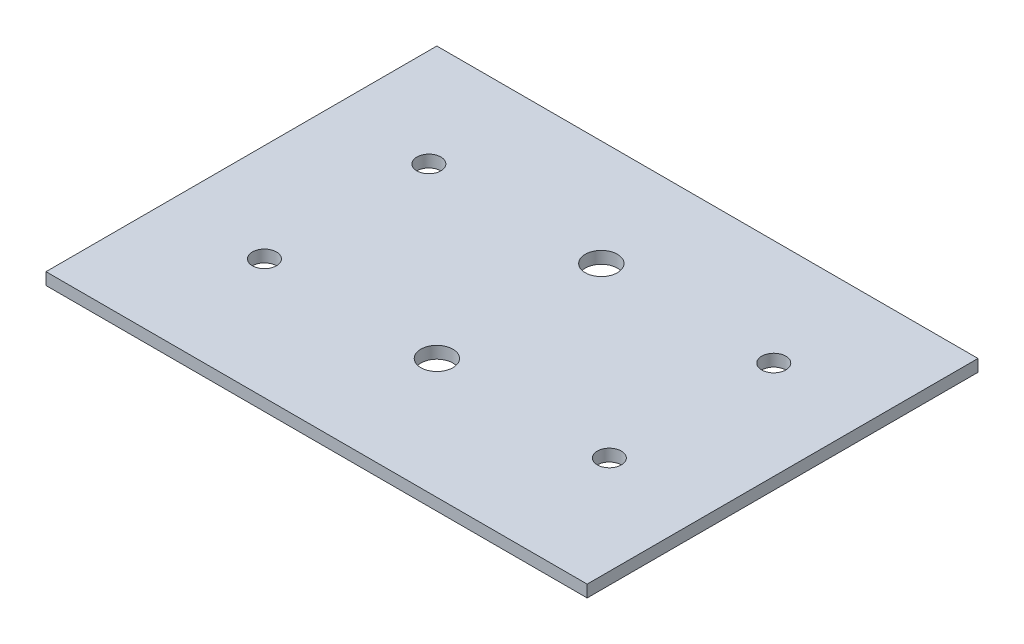
SolidWorks part; units mm, degrees
ref_plane "Front Plane" through (0, 0, 0) normal (0, 0, 1) x (1, 0, 0)
ref_plane "Top Plane" through (0, 0, 0) normal (0, 1, 0) x (1, 0, 0)
ref_plane "Right Plane" through (0, 0, 0) normal (1, 0, 0) x (0, 0, -1)
sketch "Sketch1" plane through (0, 0, 0) normal (0, 1, 0) x (1, 0, 0)
  line L0 (0, 1218.2255) -> (0, -1218.2255) construction
  line L1 (-1686.7738, 1218.2255) -> (1686.7738, 1218.2255)
  line L2 (-1686.7738, 1218.2255) -> (-1686.7738, -1218.2255)
  line L3 (-1686.7738, -1218.2255) -> (1686.7738, -1218.2255)
  line L4 (1686.7738, 1218.2255) -> (1686.7738, -1218.2255)
  line L5 (-1686.7738, 1218.2255) -> (1686.7738, -1218.2255) construction
  line L6 (-1686.7738, -1218.2255) -> (1686.7738, 1218.2255) construction
  line L7 (-1686.7738, 0) -> (1686.7738, 0) construction
  circle A0 centre (1075, -468.2255) radius 75
  circle A1 centre (1075, 556.7745) radius 75
  circle A2 centre (-1075, -468.2255) radius 75
  circle A3 centre (-1075, 556.7745) radius 75
  circle A4 centre (0, -468.2255) radius 100
  circle A5 centre (0, 556.7745) radius 100
  point P0 (0, 0)
  point P22 (0, 0)
  dimension "D1" = 1075
  dimension "D3" = 150
  dimension "D4" = 1025
  dimension "D6" = 200
  dimension "D7" = 200
  dimension "D2" = 750
  dimension "D5" = 1075
  dimension "D8" = 750
  dimension "D9" = 1025
extrude "Boss-Extrude1" add sketch "Sketch1" along normal blind 75
